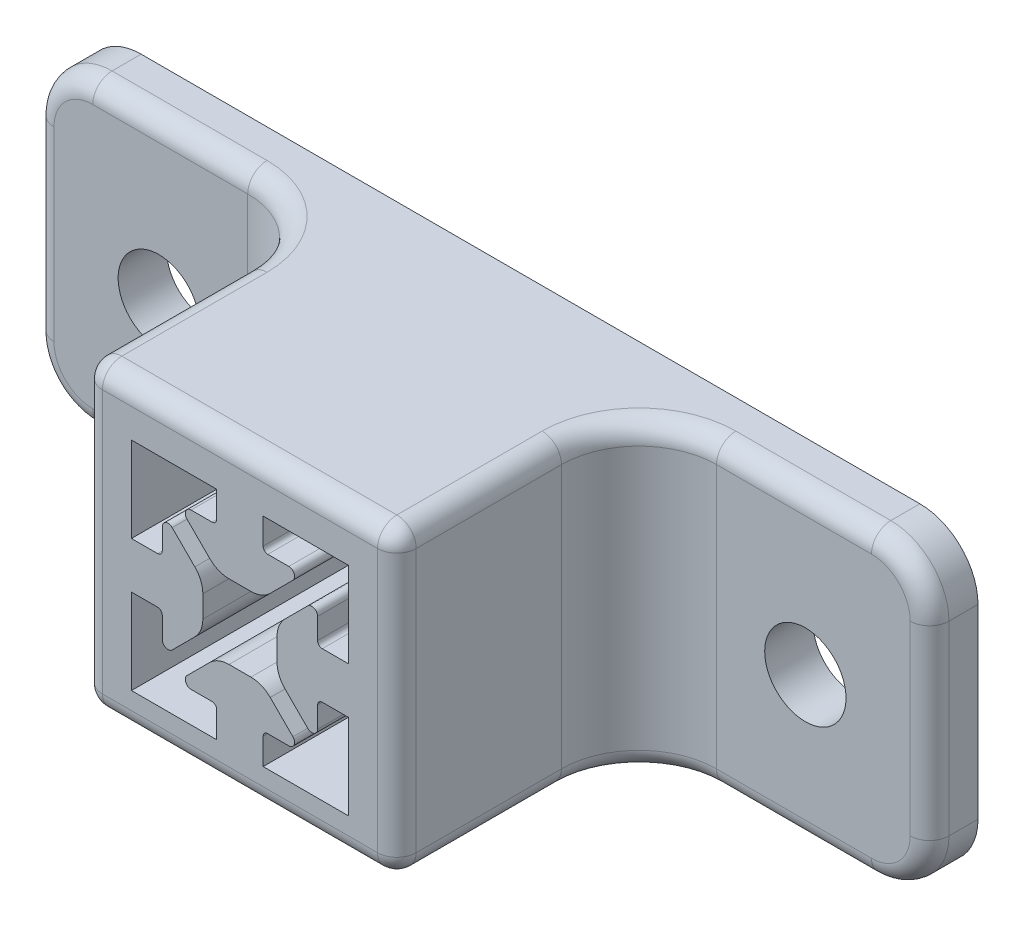
SolidWorks part; units mm, degrees
ref_plane "Front Plane" through (0, 0, 0) normal (0, 0, 1) x (1, 0, 0)
ref_plane "Top Plane" through (0, 0, 0) normal (0, 1, 0) x (1, 0, 0)
ref_plane "Right Plane" through (0, 0, 0) normal (1, 0, 0) x (0, 0, -1)
ref_plane "Plane1" through (0, 0, -1358.9406) normal (0, 0, 1) x (1, 0, 0)
sketch "Sketch2" plane through (0, 0, -1358.9406) normal (0, 0, 1) x (1, 0, 0)
  line L7 (-219.4843, 633.65) -> (-221.7534, 633.65) construction
  line L8 (-223.8747, 634.5287) -> (-226.2145, 636.8685) construction
  line L9 (-215.0232, 636.8685) -> (-217.363, 634.5287) construction
  line L10 (-217.7438, 638.2) -> (-215.5747, 638.2) construction
  line L11 (-218.0438, 639.2) -> (-218.0438, 638.5) construction
  line L12 (-223.1938, 638.5) -> (-223.1938, 639.2) construction
  line L13 (-225.663, 638.2) -> (-223.4938, 638.2) construction
  line L14 (-218.2238, 639.2) -> (-218.2238, 638.5)
  line L15 (-217.7438, 638.02) -> (-215.5747, 638.02)
  line L16 (-215.1505, 636.9957) -> (-217.4902, 634.656)
  line L17 (-219.4843, 633.83) -> (-221.7534, 633.83)
  line L18 (-223.7475, 634.656) -> (-226.0872, 636.9957)
  line L19 (-225.663, 638.02) -> (-223.4938, 638.02)
  line L20 (-223.0138, 638.5) -> (-223.0138, 639.2)
  line L21 (-220.6188, 630) -> (-220.6188, 642.8124) construction
  line L22 (-220.6188, 630) -> (-207.2782, 630) construction
  line L23 (-212.5988, 635.0441) -> (-212.5988, 632.875)
  line L24 (-215.9629, 633.1286) -> (-213.6231, 635.4684)
  line L25 (-216.7888, 628.8654) -> (-216.7888, 631.1346)
  line L26 (-212.5988, 627.125) -> (-212.5988, 624.9559)
  line L27 (-211.4188, 627.605) -> (-212.1188, 627.605)
  line L28 (-213.6231, 624.5316) -> (-215.9629, 626.8714)
  line L29 (-212.1188, 632.395) -> (-211.4188, 632.395)
  line L30 (-215.5747, 621.98) -> (-217.7438, 621.98)
  line L31 (-217.4902, 625.344) -> (-215.1505, 623.0043)
  line L32 (-221.7534, 626.17) -> (-219.4843, 626.17)
  line L33 (-223.4938, 621.98) -> (-225.663, 621.98)
  line L34 (-223.0138, 620.8) -> (-223.0138, 621.5)
  line L35 (-226.0872, 623.0043) -> (-223.7475, 625.344)
  line L36 (-218.2238, 621.5) -> (-218.2238, 620.8)
  line L37 (-228.6388, 624.9559) -> (-228.6388, 627.125)
  line L38 (-225.2748, 626.8714) -> (-227.6146, 624.5316)
  line L39 (-224.4488, 631.1346) -> (-224.4488, 628.8654)
  line L40 (-228.6388, 632.875) -> (-228.6388, 635.0441)
  line L41 (-229.8188, 632.395) -> (-229.1188, 632.395)
  line L42 (-227.6146, 635.4684) -> (-225.2748, 633.1286)
  line L43 (-229.1188, 627.605) -> (-229.8188, 627.605)
  line L44 (-231.8188, 618.8) -> (-231.8188, 627.605)
  line L46 (-223.0138, 620.8) -> (-223.0138, 618.8)
  line L47 (-223.0138, 618.8) -> (-231.8188, 618.8)
  line L49 (-231.8188, 641.2) -> (-223.0138, 641.2)
  line L50 (-229.8188, 627.605) -> (-231.8188, 627.605)
  line L51 (-229.8188, 632.395) -> (-231.8188, 632.395)
  line L52 (-231.8188, 632.395) -> (-231.8188, 641.2)
  line L54 (-209.4188, 618.8) -> (-209.4188, 627.605)
  line L55 (-211.4188, 627.605) -> (-209.4188, 627.605)
  line L56 (-211.4188, 632.395) -> (-209.4188, 632.395)
  line L57 (-209.4188, 632.395) -> (-209.4188, 641.2)
  line L59 (-218.2238, 618.8) -> (-209.4188, 618.8)
  line L60 (-223.0138, 639.2) -> (-223.0138, 641.2)
  line L61 (-218.2238, 639.2) -> (-218.2238, 641.2)
  line L62 (-218.2238, 641.2) -> (-209.4188, 641.2)
  line L64 (-236.8188, 646.2) -> (-204.4188, 646.2)
  line L65 (-236.8188, 646.2) -> (-236.8188, 615)
  line L66 (-236.8188, 615) -> (-204.4188, 615)
  line L67 (-204.4188, 646.2) -> (-204.4188, 615)
  line L68 (-218.2238, 620.8) -> (-218.2238, 618.8)
  arc A6 (-219.4843, 633.65) -> (-217.363, 634.5287) centre (-219.4843, 636.65) ccw construction
  arc A7 (-223.8747, 634.5287) -> (-221.7534, 633.65) centre (-221.7534, 636.65) ccw construction
  arc A8 (-215.0232, 636.8685) -> (-215.5747, 638.2) centre (-215.5747, 637.42) ccw construction
  arc A9 (-218.0438, 638.5) -> (-217.7438, 638.2) centre (-217.7438, 638.5) ccw construction
  arc A10 (-223.4938, 638.2) -> (-223.1938, 638.5) centre (-223.4938, 638.5) ccw construction
  arc A11 (-225.663, 638.2) -> (-226.2145, 636.8685) centre (-225.663, 637.42) ccw construction
  arc A12 (-218.2238, 638.5) -> (-217.7438, 638.02) centre (-217.7438, 638.5) ccw
  arc A13 (-215.1505, 636.9957) -> (-215.5747, 638.02) centre (-215.5747, 637.42) ccw
  arc A14 (-219.4843, 633.83) -> (-217.4902, 634.656) centre (-219.4843, 636.65) ccw
  arc A15 (-223.7475, 634.656) -> (-221.7534, 633.83) centre (-221.7534, 636.65) ccw
  arc A16 (-225.663, 638.02) -> (-226.0872, 636.9957) centre (-225.663, 637.42) ccw
  arc A17 (-223.4938, 638.02) -> (-223.0138, 638.5) centre (-223.4938, 638.5) ccw
  arc A18 (-212.5988, 635.0441) -> (-213.6231, 635.4684) centre (-213.1988, 635.0441) ccw
  arc A19 (-215.9629, 633.1286) -> (-216.7888, 631.1346) centre (-213.9688, 631.1346) ccw
  arc A20 (-216.7888, 628.8654) -> (-215.9629, 626.8714) centre (-213.9688, 628.8654) ccw
  arc A21 (-213.6231, 624.5316) -> (-212.5988, 624.9559) centre (-213.1988, 624.9559) ccw
  arc A22 (-212.1188, 627.605) -> (-212.5988, 627.125) centre (-212.1188, 627.125) ccw
  arc A23 (-212.5988, 632.875) -> (-212.1188, 632.395) centre (-212.1188, 632.875) ccw
  arc A24 (-215.5747, 621.98) -> (-215.1505, 623.0043) centre (-215.5747, 622.58) ccw
  arc A25 (-217.4902, 625.344) -> (-219.4843, 626.17) centre (-219.4843, 623.35) ccw
  arc A26 (-221.7534, 626.17) -> (-223.7475, 625.344) centre (-221.7534, 623.35) ccw
  arc A27 (-226.0872, 623.0043) -> (-225.663, 621.98) centre (-225.663, 622.58) ccw
  arc A28 (-223.0138, 621.5) -> (-223.4938, 621.98) centre (-223.4938, 621.5) ccw
  arc A29 (-217.7438, 621.98) -> (-218.2238, 621.5) centre (-217.7438, 621.5) ccw
  arc A30 (-228.6388, 624.9559) -> (-227.6146, 624.5316) centre (-228.0388, 624.9559) ccw
  arc A31 (-225.2748, 626.8714) -> (-224.4488, 628.8654) centre (-227.2688, 628.8654) ccw
  arc A32 (-224.4488, 631.1346) -> (-225.2748, 633.1286) centre (-227.2688, 631.1346) ccw
  arc A33 (-227.6146, 635.4684) -> (-228.6388, 635.0441) centre (-228.0388, 635.0441) ccw
  arc A34 (-229.1188, 632.395) -> (-228.6388, 632.875) centre (-229.1188, 632.875) ccw
  arc A35 (-228.6388, 627.125) -> (-229.1188, 627.605) centre (-229.1188, 627.125) ccw
  dimension "D5" = 5
  dimension "D6" = 5
  dimension "D7" = 5
  dimension "D1" = 0.18
  dimension "D2" = 4
extrude "Boss-Extrude1" add sketch "Sketch2" along normal blind 30
ref_plane "Plane2" through (-204.4188, 0, 0) normal (1, 0, 0) x (0, 0, -1)
sketch "Sketch3" plane through (-204.4188, 0, 0) normal (1, 0, 0) x (0, 0, -1)
  line L1 (1358.9406, 646.2) -> (1353.9406, 646.2)
  line L2 (1358.9406, 646.2) -> (1358.9406, 615)
  line L3 (1358.9406, 615) -> (1353.9406, 615)
  line L4 (1353.9406, 646.2) -> (1353.9406, 615)
  dimension "D1" = 5
ref_plane "Plane3" through (-220.6188, 0, 0) normal (1, 0, 0) x (0, 0, -1)
extrude "Boss-Extrude2" add sketch "Sketch3" along normal blind 30
ref_plane "Plane4" through (0, 0, -1353.9406) normal (0, 0, 1) x (1, 0, 0)
sketch "Sketch4" plane through (0, 0, -1353.9406) normal (0, 0, 1) x (1, 0, 0)
  line L4 (-183.0688, 584.25) -> (-183.0688, 675.75) construction
  line L5 (-191.4188, 675.75) -> (-191.4188, 584.25) construction
  line L6 (-183.0688, 584.25) -> (-183.0688, 675.75) construction
  line L7 (-191.4188, 675.75) -> (-191.4188, 584.25) construction
  line L8 (-191.4188, 630) -> (-183.0688, 630) construction
  circle A4 centre (-187.2438, 630) radius 4.1985
  dimension "D1" = 8.3969
extrude "Cut-Extrude1" cut sketch "Sketch4" against normal mid plane 30
mirror "Mirror6" about plane through (-220.6188, 0, 0) normal (1, 0, 0) of "Boss-Extrude2"
mirror "Mirror9" about plane through (-220.6188, 0, 0) normal (1, 0, 0) of "Cut-Extrude1"
fillet "Fillet6" radius 8 2 edges at (-236.8188, 630.6, -1353.9406) (-204.4188, 630.6, -1353.9406)
fillet "Fillet7" radius 6 4 edges at (-266.8188, 615, -1356.4406) (-266.8188, 646.2, -1356.4406) (-174.4188, 615, -1356.4406) (-174.4188, 646.2, -1356.4406)
fillet "Fillet8" radius 2 22 edges at (-204.4188, 630.6, -1328.9406) (-220.6188, 646.2, -1328.9406) (-239.162, 615, -1351.5975) (-239.162, 646.2, -1351.5975) (-202.0757, 615, -1351.5975) (-202.0757, 646.2, -1351.5975) (-188.4188, 615, -1353.9406) (-252.8188, 615, -1353.9406) (-266.8188, 630.6, -1353.9406) (-252.8188, 646.2, -1353.9406) (-265.0615, 644.4426, -1353.9406) (-265.0615, 616.7574, -1353.9406) (-188.4188, 646.2, -1353.9406) (-174.4188, 630.6, -1353.9406) (-176.1762, 644.4426, -1353.9406) (-176.1762, 616.7574, -1353.9406) (-236.8188, 630.6, -1328.9406) (-236.8188, 646.2, -1337.4406) (-204.4188, 646.2, -1337.4406) (-204.4188, 615, -1337.4406) (-236.8188, 615, -1337.4406) (-220.6188, 615, -1328.9406)
